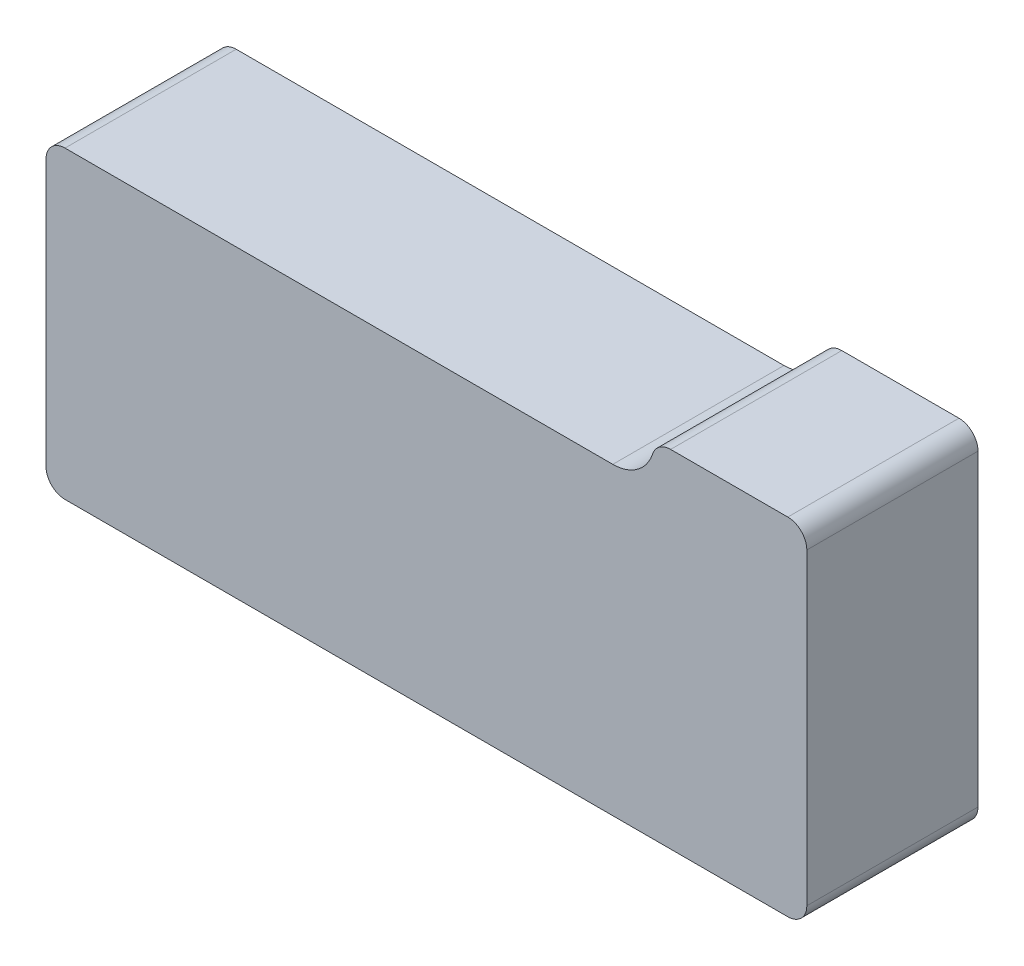
SolidWorks part; units mm, degrees
ref_plane "Plane1" through (0, 0, 0) normal (0, 0, 1) x (1, 0, 0)
ref_plane "Plane2" through (0, 0, 0) normal (0, 1, 0) x (1, 0, 0)
ref_plane "Plane3" through (0, 0, 0) normal (1, 0, 0) x (0, 0, -1)
sketch "Sketch1" plane through (0, 0, 0) normal (0, 0, 1) x (1, 0, 0)
  line L0 (100, 0) -> (-100, 0) construction
  line L1 (-95, 40) -> (49, 40)
  line L2 (-100, 35) -> (-100, -35)
  line L3 (-95, -40) -> (95, -40)
  line L4 (100, 46) -> (100, -35)
  line L5 (95, 51) -> (64.1987, 51)
  line L6 (0, 0) -> (0, 15.7241) construction
  arc A0 (-95, 40) -> (-100, 35) centre (-95, 35) ccw
  arc A1 (-100, -35) -> (-95, -40) centre (-95, -35) ccw
  arc A2 (95, -40) -> (100, -35) centre (95, -35) ccw
  arc A3 (59.4491, 47.5625) -> (64.1987, 51) centre (64.1987, 46) cw
  arc A4 (49, 40) -> (59.4491, 47.5625) centre (49, 51) ccw
  arc A5 (100, 46) -> (95, 51) centre (95, 46) ccw
  point P21 (60, 51)
  dimension "D1" = 5
  dimension "D5" = 40
  dimension "D6" = 11
  dimension "D7" = 5
  dimension "D8" = 5
  dimension "D2" = 200
  dimension "D3" = 11
  dimension "D4" = 80
extrude "Extrude1" add sketch "Sketch1" along normal blind 45
sketch "Heater path" plane through (91.2746, -269.023, 0) normal (0, 0, -1) x (-1, 0, 0)
  line L0 (16.7805, 334.023) -> (16.7805, 311.023)
  line L1 (-1.2195, 334.023) -> (-1.2195, 257.523)
  line L4 (162.735, 299.023) -> (162.735, 239.023) construction
  line L5 (17.2805, 299.023) -> (17.2805, 239.023) construction
  line L7 (35.6628, 296.5341) -> (43.044, 298.5119)
  line L8 (-8.7254, 269.023) -> (191.2746, 269.023) construction
  line L9 (46.9263, 299.023) -> (162.735, 299.023)
  line L10 (162.735, 239.023) -> (17.2805, 239.023)
  line L11 (181.235, 280.523) -> (181.235, 257.523)
  line L13 (17.2805, 269.023) -> (162.735, 269.023) construction
  line L14 (42.2746, 309.023) -> (186.2746, 309.023) construction
  arc A4 (162.735, 299.023) -> (181.235, 280.523) centre (162.735, 280.523) cw
  arc A5 (-1.2195, 257.523) -> (17.2805, 239.023) centre (17.2805, 257.523) ccw
  arc A7 (162.735, 239.023) -> (181.235, 257.523) centre (162.735, 257.523) ccw
  arc A9 (43.044, 298.5119) -> (46.9263, 299.023) centre (46.9263, 284.023) cw
  arc A10 (35.6628, 296.5341) -> (16.7805, 311.023) centre (31.7805, 311.023) cw
  point P3 (90.0078, 269.023)
  point P10 (0, 0)
  dimension "D2" = 15
  dimension "D4" = 15
  dimension "D3" = 15
  dimension "D6" = 60
  dimension "D8" = 12
  dimension "D9" = 18.5
  dimension "D10" = 35
  dimension "D11" = 18.5
  dimension "D7" = 145.4545
  dimension "D13" = 35
  dimension "D5" = 18
